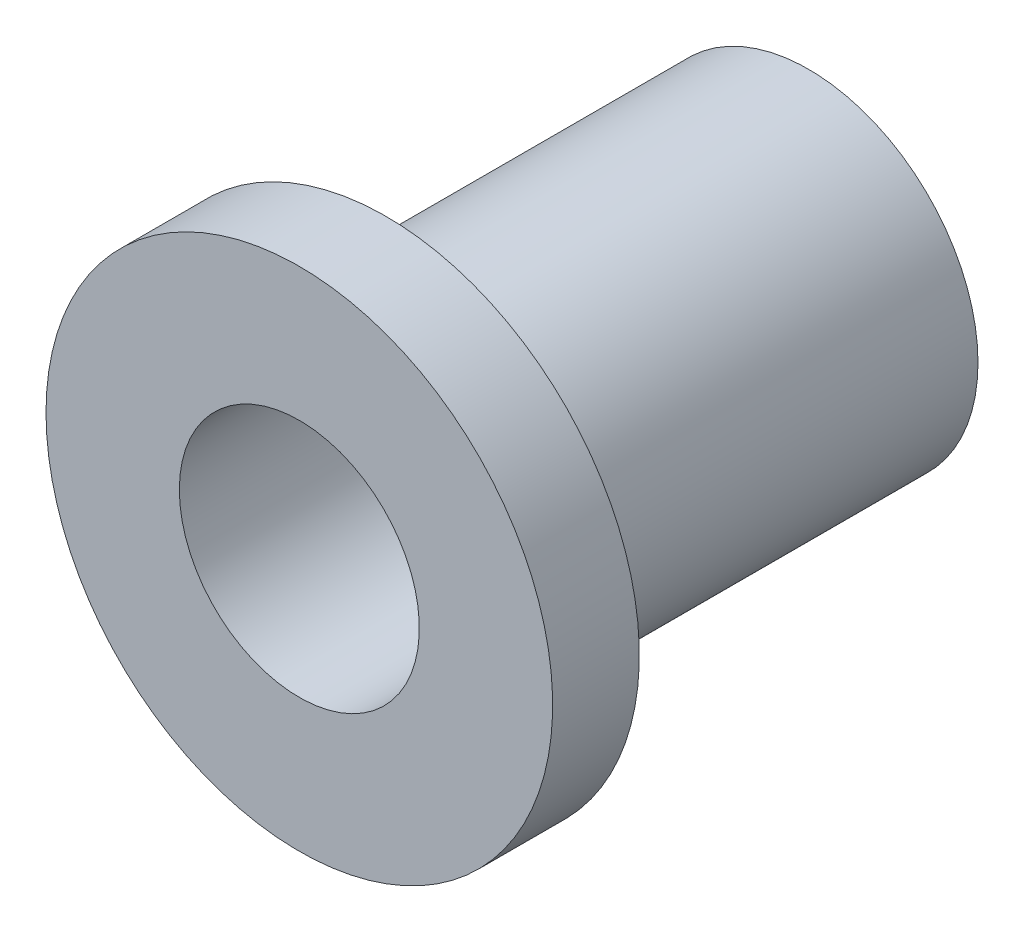
SolidWorks part; units mm, degrees
ref_plane "Спереди" through (0, 0, 0) normal (0, 0, 1) x (1, 0, 0)
ref_plane "Сверху" through (0, 0, 0) normal (0, 1, 0) x (1, 0, 0)
ref_plane "Справа" through (0, 0, 0) normal (1, 0, 0) x (0, 0, -1)
sketch "Эскиз1" plane through (0, 0, 0) normal (0, 0, 1) x (1, 0, 0)
  circle A0 centre (0, 0) radius 9.5
  circle A1 centre (0, 0) radius 4.5
  dimension "D1" = 19
  dimension "D2" = 9
extrude "Бобышка-Вытянуть1" add sketch "Эскиз1" along normal blind 3.25
sketch "Эскиз2" plane through (0, 0, 0) normal (0, 0, -1) x (-1, 0, 0)
  circle A1 centre (0, 0) radius 6.35
  circle A2 centre (0, 0) radius 4.5
  dimension "D1" = 12.7
extrude "Бобышка-Вытянуть2" add sketch "Эскиз2" along normal blind 15.85
